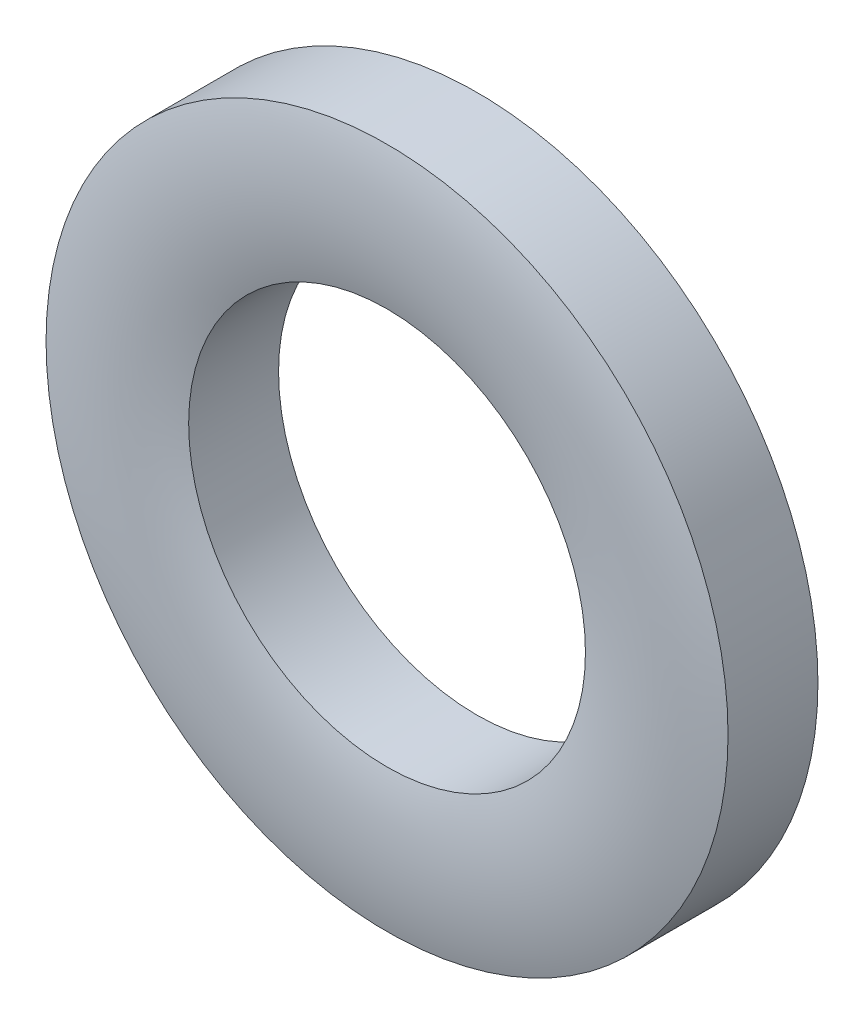
SolidWorks part; units mm, degrees
ref_plane "Front Plane" through (0, 0, 0) normal (0, 0, 1) x (1, 0, 0)
ref_plane "Top Plane" through (0, 0, 0) normal (0, 1, 0) x (1, 0, 0)
ref_plane "Right Plane" through (0, 0, 0) normal (1, 0, 0) x (0, 0, -1)
sketch "Sketch1" plane through (0, 0, 0) normal (0, 0, 1) x (1, 0, 0)
  circle A0 centre (0, 0) radius 3.2
  circle A1 centre (0, 0) radius 5.5
  dimension "ID" = 6.4
  dimension "OD" = 11
sketch "Sketch2" plane through (0, 0, 0) normal (1, 0, 0) x (0, 0, -1)
  line L0 (-0.8, 5.5) -> (0.8, 5.5) construction
  line L1 (-0.8, 0) -> (0.8, 0) construction
  point P2 (0, 5.5)
  dimension "Thickness Range" = 1.6
sketch "Sketch3" plane through (0, 0, 0) normal (1, 0, 0) x (0, 0, -1)
  line L0 (0.8, 5.5) -> (-0.6501, 5.5)
  line L1 (0.8, 3.2) -> (-0.6501, 3.2)
  line L2 (0.8, 3.2) -> (0.8, 5.5)
  line L3 (-0.8, 5.5) -> (-0.8, 3.2) construction
  arc A0 (-0.6501, 3.2) -> (-0.6501, 5.5) centre (3.6856, 4.35) cw
  point P9 (0, 3.2)
  dimension "D1" = 0.1499
revolve "Revolve1" add sketch "Sketch3" angle 360 about L1
equation "\"D1@Sketch3\"=\"Thickness Range@Sketch2\"*.0937"
